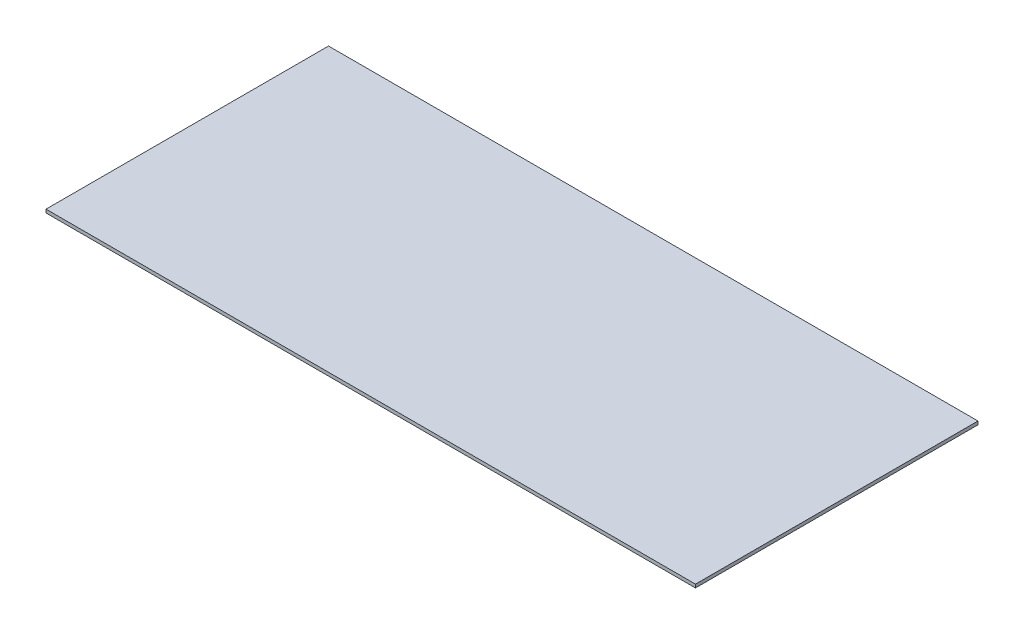
SolidWorks part; units mm, degrees
ref_plane "Front Plane" through (0, 0, 0) normal (0, 0, 1) x (1, 0, 0)
ref_plane "Top Plane" through (0, 0, 0) normal (0, 1, 0) x (1, 0, 0)
ref_plane "Right Plane" through (0, 0, 0) normal (1, 0, 0) x (0, 0, -1)
sketch "Sketch1" plane through (0, 0, 0) normal (0, 1, 0) x (1, 0, 0)
  line L1 (-194.25, 84.5) -> (194.25, 84.5)
  line L2 (-194.25, 84.5) -> (-194.25, -84.5)
  line L3 (-194.25, -84.5) -> (194.25, -84.5)
  line L4 (194.25, 84.5) -> (194.25, -84.5)
  line L5 (-194.25, 84.5) -> (194.25, -84.5) construction
  line L6 (-194.25, -84.5) -> (194.25, 84.5) construction
  point P0 (0, 0)
  dimension "D1" = 388.5
  dimension "D2" = 169
extrude "Boss-Extrude1" add sketch "Sketch1" along normal blind 2
